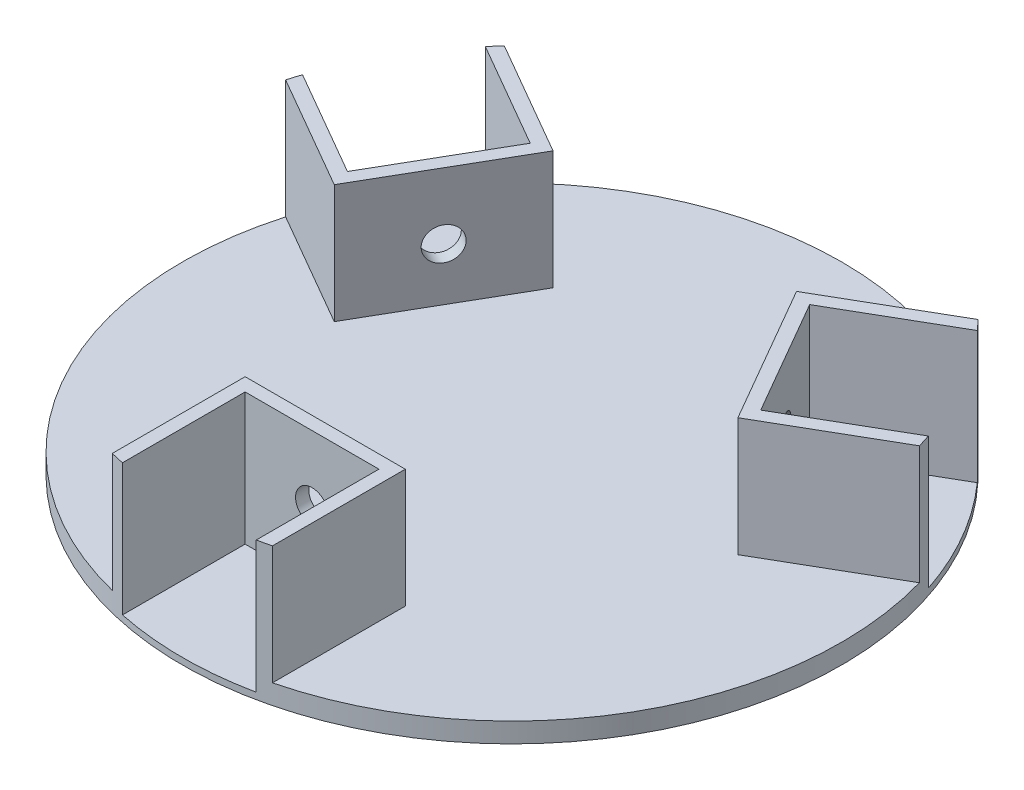
SolidWorks part; units mm, degrees
ref_plane "Front Plane" through (0, 0, 0) normal (0, 0, 1) x (1, 0, 0)
ref_plane "Top Plane" through (0, 0, 0) normal (0, 1, 0) x (1, 0, 0)
ref_plane "Right Plane" through (0, 0, 0) normal (1, 0, 0) x (0, 0, -1)
sketch "Sketch1" plane through (0, 0, 0) normal (0, 1, 0) x (1, 0, 0)
  line L0 (-30, -18) -> (30, -18) construction
  line L1 (-30, 10) -> (-22.5, 10) construction
  line L2 (-46.46, 5.4904) -> (-53.96, -7.5) construction
  line L3 (-30, -10) -> (-22.5, -10) construction
  line L4 (30, 10) -> (30, 2.5) construction
  line L5 (0, 0) -> (0, -75.5561) construction
  line L6 (38.6603, -23) -> (65.7735, -69.9615) construction
  line L7 (65.7735, -69.9615) -> (68.3716, -68.4615) construction
  line L8 (69.1036, -65.7295) -> (41.8357, -18.5) construction
  line L9 (43.1036, -13.7679) -> (55.6921, -6.5) construction
  line L10 (56.4241, -3.7679) -> (51.362, 5) construction
  line L11 (25.3812, 20) -> (-25.3812, 20) construction
  line L12 (43.5677, -13.5) -> (36.0677, -0.5096) construction
  line L13 (36.0677, -0.5096) -> (46.46, 5.4904) construction
  line L14 (46.46, 5.4904) -> (53.96, -7.5) construction
  line L15 (-36.0677, -0.5096) -> (-46.46, 5.4904) construction
  line L16 (-43.5677, -13.5) -> (-36.0677, -0.5096) construction
  line L17 (-56.4241, -3.7679) -> (-51.362, 5) construction
  line L18 (-43.1036, -13.7679) -> (-55.6921, -6.5) construction
  line L19 (-69.1036, -65.7295) -> (-41.8357, -18.5) construction
  line L20 (-65.7735, -69.9615) -> (-68.3716, -68.4615) construction
  line L21 (-38.6603, -23) -> (-65.7735, -69.9615) construction
  line L22 (-30, 10) -> (-30, 2.5) construction
  line L23 (30, 2.5) -> (25, 2.5) construction
  line L24 (25, 2.5) -> (25, -2.5) construction
  line L25 (25, -2.5) -> (30, -2.5) construction
  line L26 (30, -2.5) -> (30, -10) construction
  line L27 (22.5, -10) -> (22.5, -5) construction
  line L28 (22.5, -5) -> (17.5, -5) construction
  line L29 (17.5, -5) -> (17.5, -10) construction
  line L30 (22.5, -10) -> (30, -10) construction
  line L31 (17.5, 10) -> (17.5, 9) construction
  line L32 (17.5, 9) -> (22.5, 9) construction
  line L33 (22.5, 9) -> (22.5, 10) construction
  line L34 (22.5, 10) -> (30, 10) construction
  line L35 (2.5, -10) -> (2.5, -5) construction
  line L36 (2.5, -5) -> (-2.5, -5) construction
  line L37 (-2.5, -5) -> (-2.5, -10) construction
  line L38 (-2.5, 10) -> (-2.5, 9) construction
  line L39 (-2.5, 9) -> (2.5, 9) construction
  line L40 (2.5, 9) -> (2.5, 10) construction
  line L41 (-17.5, -10) -> (-17.5, -5) construction
  line L42 (-17.5, -5) -> (-22.5, -5) construction
  line L43 (-22.5, -5) -> (-22.5, -10) construction
  line L44 (-22.5, 10) -> (-22.5, 9) construction
  line L45 (-22.5, 9) -> (-17.5, 9) construction
  line L46 (-17.5, 9) -> (-17.5, 10) construction
  line L47 (-17.5, 10) -> (-2.5, 10) construction
  line L48 (-17.5, -10) -> (-2.5, -10) construction
  line L49 (2.5, -10) -> (17.5, -10) construction
  line L50 (2.5, 10) -> (17.5, 10) construction
  line L51 (-25, -2.5) -> (-30, -2.5) construction
  line L52 (-25, 2.5) -> (-25, -2.5) construction
  line L53 (-30, 2.5) -> (-25, 2.5) construction
  line L54 (-30, -2.5) -> (-30, -10) construction
  line L55 (207.8868, -326.1089) -> (177.8868, -378.0704) construction
  line L56 (232.1355, -340.1089) -> (228.3855, -346.6041) construction
  line L57 (236.46, -323.5993) -> (228.96, -310.6089) construction
  line L58 (214.815, -330.1089) -> (211.065, -336.6041) construction
  line L59 (202.1355, -392.0704) -> (195.6403, -388.3204) construction
  line L60 (169.2265, -383.0704) -> (115, -383.0704) construction
  line L61 (115, -383.0704) -> (115, -386.0704) construction
  line L62 (117, -388.0704) -> (171.5359, -388.0704) construction
  line L63 (175, -391.5345) -> (175, -406.0704) construction
  line L64 (177, -408.0704) -> (187.1244, -408.0704) construction
  line L65 (213.1051, -393.0704) -> (238.4863, -349.1089) construction
  line L66 (175, -392.0704) -> (190, -392.0704) construction
  line L67 (190, -392.0704) -> (190, -404.0704) construction
  line L68 (190, -404.0704) -> (175, -404.0704) construction
  line L69 (226.0677, -329.5993) -> (236.46, -323.5993) construction
  line L70 (218.5677, -316.6089) -> (226.0677, -329.5993) construction
  line L71 (233.4241, -310.3409) -> (238.4863, -319.1089) construction
  line L72 (218.1036, -316.8768) -> (230.6921, -309.6089) construction
  line L73 (186.1036, -268.3794) -> (213.3716, -315.6089) construction
  line L74 (180.7735, -269.1474) -> (183.3716, -267.6474) construction
  line L75 (207.8868, -316.1089) -> (180.7735, -269.1474) construction
  line L76 (232.1355, -340.1089) -> (225.6403, -336.3589) construction
  line L77 (195.6403, -388.3204) -> (198.1403, -383.9903) construction
  line L78 (198.1403, -383.9903) -> (193.8101, -381.4903) construction
  line L79 (193.8101, -381.4903) -> (191.3101, -385.8204) construction
  line L80 (191.3101, -385.8204) -> (184.815, -382.0704) construction
  line L81 (188.565, -375.5752) -> (192.8951, -378.0752) construction
  line L82 (192.8951, -378.0752) -> (195.3951, -373.7451) construction
  line L83 (195.3951, -373.7451) -> (191.065, -371.2451) construction
  line L84 (188.565, -375.5752) -> (184.815, -382.0704) construction
  line L85 (208.3855, -381.2451) -> (207.5194, -380.7451) construction
  line L86 (207.5194, -380.7451) -> (205.0194, -385.0752) construction
  line L87 (205.0194, -385.0752) -> (205.8855, -385.5752) construction
  line L88 (205.8855, -385.5752) -> (202.1355, -392.0704) construction
  line L89 (198.565, -358.2547) -> (202.8951, -360.7547) construction
  line L90 (202.8951, -360.7547) -> (205.3951, -356.4246) construction
  line L91 (205.3951, -356.4246) -> (201.065, -353.9246) construction
  line L92 (218.3855, -363.9246) -> (217.5194, -363.4246) construction
  line L93 (217.5194, -363.4246) -> (215.0194, -367.7547) construction
  line L94 (215.0194, -367.7547) -> (215.8855, -368.2547) construction
  line L95 (208.565, -340.9342) -> (212.8951, -343.4342) construction
  line L96 (212.8951, -343.4342) -> (215.3951, -339.1041) construction
  line L97 (215.3951, -339.1041) -> (211.065, -336.6041) construction
  line L98 (228.3855, -346.6041) -> (227.5194, -346.1041) construction
  line L99 (227.5194, -346.1041) -> (225.0194, -350.4342) construction
  line L100 (225.0194, -350.4342) -> (225.8855, -350.9342) construction
  line L101 (225.8855, -350.9342) -> (218.3855, -363.9246) construction
  line L102 (208.565, -340.9342) -> (201.065, -353.9246) construction
  line L103 (198.565, -358.2547) -> (191.065, -371.2451) construction
  line L104 (215.8855, -368.2547) -> (208.3855, -381.2451) construction
  line L105 (218.8101, -338.189) -> (221.3101, -333.8589) construction
  line L106 (223.1403, -340.689) -> (218.8101, -338.189) construction
  line L107 (225.6403, -336.3589) -> (223.1403, -340.689) construction
  line L108 (221.3101, -333.8589) -> (214.815, -330.1089) construction
  line L109 (-177.8868, -378.0704) -> (-207.8868, -326.1089) construction
  line L110 (-202.1355, -392.0704) -> (-205.8855, -385.5752) construction
  line L111 (-190, -404.0704) -> (-175, -404.0704) construction
  line L112 (-184.815, -382.0704) -> (-188.565, -375.5752) construction
  line L113 (-232.1355, -340.1089) -> (-225.6403, -336.3589) construction
  line L114 (-207.8868, -316.1089) -> (-180.7735, -269.1474) construction
  line L115 (-180.7735, -269.1474) -> (-183.3716, -267.6474) construction
  line L116 (-186.1036, -268.3794) -> (-213.3716, -315.6089) construction
  line L117 (-218.1036, -316.8768) -> (-230.6921, -309.6089) construction
  line L118 (-233.4241, -310.3409) -> (-238.4863, -319.1089) construction
  line L119 (-238.4863, -349.1089) -> (-213.1051, -393.0704) construction
  line L120 (-218.5677, -316.6089) -> (-226.0677, -329.5993) construction
  line L121 (-226.0677, -329.5993) -> (-236.46, -323.5993) construction
  line L122 (-236.46, -323.5993) -> (-228.96, -310.6089) construction
  line L123 (-190, -392.0704) -> (-190, -404.0704) construction
  line L124 (-175, -392.0704) -> (-190, -392.0704) construction
  line L125 (-177, -408.0704) -> (-187.1244, -408.0704) construction
  line L126 (-175, -391.5345) -> (-175, -406.0704) construction
  line L127 (-117, -388.0704) -> (-171.5359, -388.0704) construction
  line L128 (-115, -383.0704) -> (-115, -386.0704) construction
  line L129 (-169.2265, -383.0704) -> (-115, -383.0704) construction
  line L130 (-202.1355, -392.0704) -> (-195.6403, -388.3204) construction
  line L131 (-225.6403, -336.3589) -> (-223.1403, -340.689) construction
  line L132 (-223.1403, -340.689) -> (-218.8101, -338.189) construction
  line L133 (-218.8101, -338.189) -> (-221.3101, -333.8589) construction
  line L134 (-221.3101, -333.8589) -> (-214.815, -330.1089) construction
  line L135 (-211.065, -336.6041) -> (-215.3951, -339.1041) construction
  line L136 (-215.3951, -339.1041) -> (-212.8951, -343.4342) construction
  line L137 (-212.8951, -343.4342) -> (-208.565, -340.9342) construction
  line L138 (-211.065, -336.6041) -> (-214.815, -330.1089) construction
  line L139 (-225.8855, -350.9342) -> (-225.0194, -350.4342) construction
  line L140 (-225.0194, -350.4342) -> (-227.5194, -346.1041) construction
  line L141 (-227.5194, -346.1041) -> (-228.3855, -346.6041) construction
  line L142 (-228.3855, -346.6041) -> (-232.1355, -340.1089) construction
  line L143 (-201.065, -353.9246) -> (-205.3951, -356.4246) construction
  line L144 (-205.3951, -356.4246) -> (-202.8951, -360.7547) construction
  line L145 (-202.8951, -360.7547) -> (-198.565, -358.2547) construction
  line L146 (-215.8855, -368.2547) -> (-215.0194, -367.7547) construction
  line L147 (-215.0194, -367.7547) -> (-217.5194, -363.4246) construction
  line L148 (-217.5194, -363.4246) -> (-218.3855, -363.9246) construction
  line L149 (-191.065, -371.2451) -> (-195.3951, -373.7451) construction
  line L150 (-195.3951, -373.7451) -> (-192.8951, -378.0752) construction
  line L151 (-192.8951, -378.0752) -> (-188.565, -375.5752) construction
  line L152 (-205.8855, -385.5752) -> (-205.0194, -385.0752) construction
  line L153 (-205.0194, -385.0752) -> (-207.5194, -380.7451) construction
  line L154 (-207.5194, -380.7451) -> (-208.3855, -381.2451) construction
  line L155 (-208.3855, -381.2451) -> (-215.8855, -368.2547) construction
  line L156 (-191.065, -371.2451) -> (-198.565, -358.2547) construction
  line L157 (-201.065, -353.9246) -> (-208.565, -340.9342) construction
  line L158 (-218.3855, -363.9246) -> (-225.8855, -350.9342) construction
  line L159 (-193.8101, -381.4903) -> (-191.3101, -385.8204) construction
  line L160 (-198.1403, -383.9903) -> (-193.8101, -381.4903) construction
  line L161 (-195.6403, -388.3204) -> (-198.1403, -383.9903) construction
  line L162 (-191.3101, -385.8204) -> (-184.815, -382.0704) construction
  line L163 (-180.7735, -269.1474) -> (-65.7735, -69.9615) construction
  line L164 (-123.2735, -169.5544) -> (-26.2787, -225.5544) construction
  line L165 (-31.3537, -234.3446) -> (-21.2037, -216.7643)
  line L166 (-21.2037, -216.7643) -> (-37.3247, -207.4568)
  line L167 (-31.3537, -234.3446) -> (-47.4747, -225.0371)
  line L168 (21.2037, -216.7643) -> (37.3247, -207.4568)
  line L169 (31.3537, -234.3446) -> (47.4747, -225.0371)
  line L170 (21.2037, -216.7643) -> (31.3537, -234.3446)
  line L171 (10.15, -271.0704) -> (10.15, -289.6854)
  line L172 (-10.15, -271.0704) -> (-10.15, -289.6854)
  line L173 (10.15, -271.0704) -> (-10.15, -271.0704)
  circle A0 centre (0, 0) radius 31.6228 construction
  arc A1 (30, -18) -> (38.6603, -23) centre (30, -28) cw construction
  arc A2 (51.362, 5) -> (25.3812, 20) centre (25.3812, -10) ccw construction
  arc A3 (41.1036, -13.7679) -> (40.1036, -17.5) centre (40.1036, -15.5) ccw construction
  arc A4 (68.3716, -68.4615) -> (69.1036, -65.7295) centre (67.3716, -66.7295) ccw construction
  arc A5 (55.6921, -6.5) -> (56.4241, -3.7679) centre (54.6921, -4.7679) ccw construction
  arc A6 (40.1036, -17.5) -> (41.8357, -18.5) centre (40.1036, -19.5) cw construction
  arc A7 (41.1036, -13.7679) -> (43.1036, -13.7679) centre (42.1036, -12.0359) ccw construction
  arc A8 (-41.1036, -13.7679) -> (-43.1036, -13.7679) centre (-42.1036, -12.0359) cw construction
  arc A9 (-40.1036, -17.5) -> (-41.8357, -18.5) centre (-40.1036, -19.5) ccw construction
  arc A10 (-55.6921, -6.5) -> (-56.4241, -3.7679) centre (-54.6921, -4.7679) cw construction
  arc A11 (-68.3716, -68.4615) -> (-69.1036, -65.7295) centre (-67.3716, -66.7295) cw construction
  arc A12 (-41.1036, -13.7679) -> (-40.1036, -17.5) centre (-40.1036, -15.5) cw construction
  arc A13 (-51.362, 5) -> (-25.3812, 20) centre (-25.3812, -10) cw construction
  arc A14 (-30, -18) -> (-38.6603, -23) centre (-30, -28) ccw construction
  arc A15 (-47.4747, -225.0371) -> (-10.15, -289.6854) centre (0, -240.7264) ccw
  arc A16 (177.8868, -378.0704) -> (169.2265, -383.0704) centre (169.2265, -373.0704) cw construction
  arc A17 (187.1244, -408.0704) -> (213.1051, -393.0704) centre (187.1244, -378.0704) ccw construction
  arc A18 (176, -389.8025) -> (173.2679, -387.0704) centre (175, -388.0704) ccw construction
  arc A19 (115, -386.0704) -> (117, -388.0704) centre (117, -386.0704) ccw construction
  arc A20 (175, -406.0704) -> (177, -408.0704) centre (177, -406.0704) ccw construction
  arc A21 (173.2679, -387.0704) -> (171.5359, -388.0704) centre (171.5359, -386.0704) cw construction
  arc A22 (176, -389.8025) -> (175, -391.5345) centre (177, -391.5345) ccw construction
  arc A23 (217.1036, -318.6089) -> (218.1036, -316.8768) centre (219.1036, -318.6089) cw construction
  arc A24 (213.3716, -317.6089) -> (213.3716, -315.6089) centre (211.6395, -316.6089) ccw construction
  arc A25 (230.6921, -309.6089) -> (233.4241, -310.3409) centre (231.6921, -311.3409) cw construction
  arc A26 (183.3716, -267.6474) -> (186.1036, -268.3794) centre (184.3716, -269.3794) cw construction
  arc A27 (217.1036, -318.6089) -> (213.3716, -317.6089) centre (215.1036, -318.6089) cw construction
  arc A28 (238.4863, -319.1089) -> (238.4863, -349.1089) centre (212.5056, -334.1089) cw construction
  arc A29 (207.8868, -326.1089) -> (207.8868, -316.1089) centre (199.2265, -321.1089) ccw construction
  arc A30 (-207.8868, -326.1089) -> (-207.8868, -316.1089) centre (-199.2265, -321.1089) cw construction
  arc A31 (-238.4863, -319.1089) -> (-238.4863, -349.1089) centre (-212.5056, -334.1089) ccw construction
  arc A32 (-217.1036, -318.6089) -> (-213.3716, -317.6089) centre (-215.1036, -318.6089) ccw construction
  arc A33 (-183.3716, -267.6474) -> (-186.1036, -268.3794) centre (-184.3716, -269.3794) ccw construction
  arc A34 (-230.6921, -309.6089) -> (-233.4241, -310.3409) centre (-231.6921, -311.3409) ccw construction
  arc A35 (-213.3716, -317.6089) -> (-213.3716, -315.6089) centre (-211.6395, -316.6089) cw construction
  arc A36 (-217.1036, -318.6089) -> (-218.1036, -316.8768) centre (-219.1036, -318.6089) ccw construction
  arc A37 (-176, -389.8025) -> (-175, -391.5345) centre (-177, -391.5345) cw construction
  arc A38 (-173.2679, -387.0704) -> (-171.5359, -388.0704) centre (-171.5359, -386.0704) ccw construction
  arc A39 (-175, -406.0704) -> (-177, -408.0704) centre (-177, -406.0704) cw construction
  arc A40 (-115, -386.0704) -> (-117, -388.0704) centre (-117, -386.0704) cw construction
  arc A41 (-176, -389.8025) -> (-173.2679, -387.0704) centre (-175, -388.0704) cw construction
  arc A42 (-187.1244, -408.0704) -> (-213.1051, -393.0704) centre (-187.1244, -378.0704) cw construction
  arc A43 (-177.8868, -378.0704) -> (-169.2265, -383.0704) centre (-169.2265, -373.0704) ccw construction
  arc A44 (37.3247, -207.4568) -> (-37.3247, -207.4568) centre (0, -240.7264) ccw
  arc A45 (10.15, -289.6854) -> (47.4747, -225.0371) centre (0, -240.7264) ccw
  point P7 (-57.4241, -5.5)
  point P9 (0, -18)
  point P22 (35.7735, -18)
  point P27 (0, 10)
  point P30 (70.1036, -67.4615)
  point P33 (57.4241, -5.5)
  point P61 (0, 20)
  point P65 (-70.1036, -67.4615)
  point P66 (-35.7735, -18)
  point P106 (232.4241, -308.6089)
  point P108 (192.8868, -352.0897)
  point P123 (217.1355, -366.0897)
  point P155 (225.7957, -371.0897)
  point P158 (185.1036, -266.6474)
  point P159 (210.7735, -321.1089)
  point P196 (-175, -408.0704)
  point P198 (-192.8868, -352.0897)
  point P213 (-217.1355, -366.0897)
  point P245 (-225.7957, -371.0897)
  point P248 (-115, -388.0704)
  point P249 (-175, -383.0704)
  point P282 (0, -240.7264)
  point P297 (0, -240.7264)
  dimension "D12" = 10
  dimension "D14" = 30
  dimension "D16" = 2
  dimension "D17" = 2
  dimension "D7" = 100
  dimension "D2" = 30
  dimension "D3" = 5
  dimension "D4" = 8
  dimension "D5" = 60
  dimension "D6" = 20
  dimension "D8" = 10
  dimension "D9" = 4
  dimension "D10" = 12
  dimension "D11" = 15
  dimension "D13" = 20
  dimension "D15" = 3
  dimension "D18" = 5
  dimension "D19" = 2.5
  dimension "D20" = 5
  dimension "D21" = 5
  dimension "D22" = 5
  dimension "D23" = 7.5
  dimension "D24" = 1
  dimension "D26" = 20
  dimension "D27" = 350
  dimension "D28" = 112
  dimension "D29" = 20.3
  dimension "D25" = 3
  dimension "D30" = 3
extrude "Boss-Extrude1" add sketch "Sketch1" along normal blind 20
shell "Shell1" thickness 2
sketch "Sketch2" plane through (0, 0, 0) normal (0, -1, 0) x (1, 0, 0)
  circle A0 centre (0, 240.7264) radius 50
  arc A1 (47.4747, 225.0371) -> (10.15, 289.6854) centre (0, 240.7264) ccw construction
extrude "Boss-Extrude2" add sketch "Sketch2" along normal blind 1
sketch "Sketch3" plane through (0, 0, 269.0704) normal (0, 0, -1) x (-1, 0, 0)
  line L0 (12.15, 20) -> (-12.15, 20) construction
  circle A0 centre (0, 10) radius 2.5
  dimension "D1" = 5
  dimension "D2" = 10
extrude "Cut-Extrude1" cut sketch "Sketch3" against normal through all
pattern_circular "CirPattern1" count 3 every 120 of "Cut-Extrude1"
